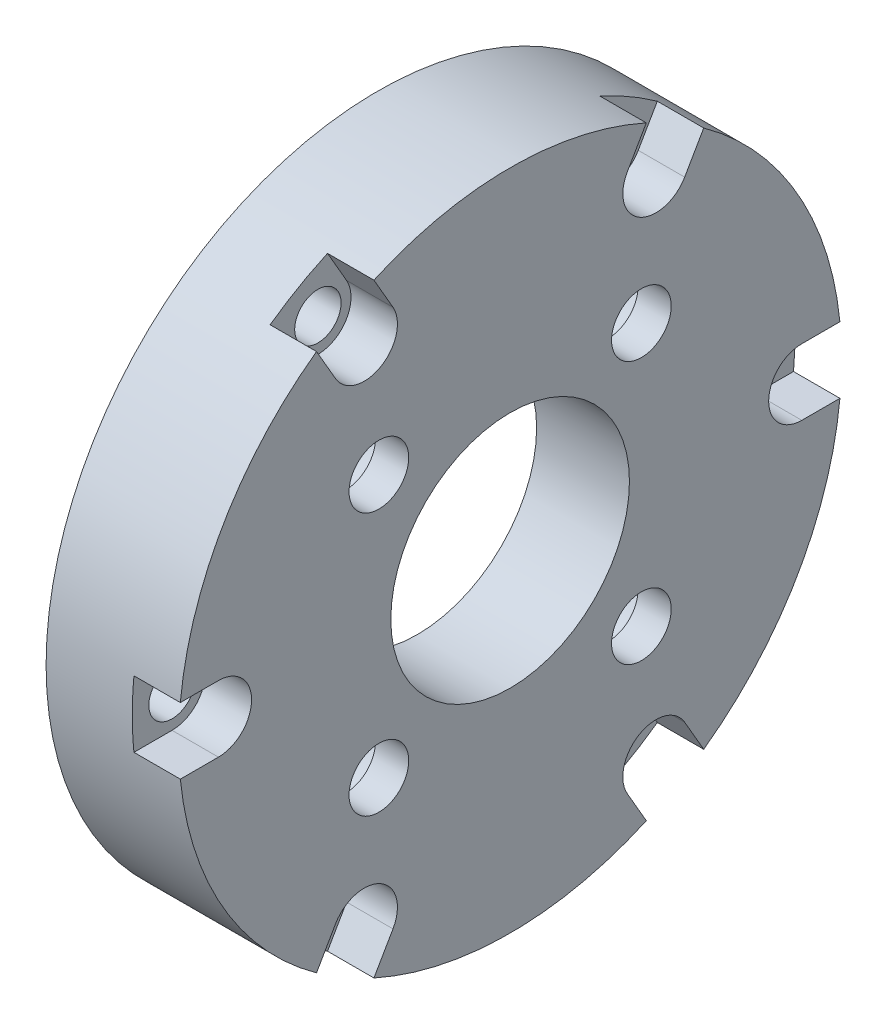
SolidWorks part; units mm, degrees
material "Alliage 1060"
ref_plane "Plan1" through (0, 0, 0) normal (0, 0, 1) x (1, 0, 0)
ref_plane "Plan2" through (0, 0, 0) normal (0, 1, 0) x (1, 0, 0)
ref_plane "Plan3" through (0, 0, 0) normal (1, 0, 0) x (0, 0, -1)
sketch "Esquisse1" plane through (0, 0, 0) normal (0, 0, 1) x (1, 0, 0)
  line L0 (-5, 25) -> (-5, 19)
  line L1 (-5, 19) -> (-2, 19)
  line L2 (-2, 19) -> (-2, 9)
  line L3 (-2, 9) -> (5, 9)
  line L4 (5, 9) -> (5, 25)
  line L5 (5, 25) -> (-5, 25)
  line L15 (-14.9364, 0) -> (44.8605, 0) construction
  dimension "D1" = 10
  dimension "D2" = 3
  dimension "D3" = 25
  dimension "D4" = 9
  dimension "D5" = 2
  dimension "D6" = 19
revolve "Base-Révolution" add sketch "Esquisse1" angle 360 about L15
sketch "Esquisse2" plane through (5, 0, 0) normal (1, 0, 0) x (0, 0, -1)
  line L0 (0, 0) -> (-24.5, 0) construction
  line L1 (-22, 2.5) -> (-25.4352, 2.5)
  line L2 (-22, -2.5) -> (-25.4352, -2.5)
  line L3 (-25.4352, -2.5) -> (-25.4352, 2.5)
  circle A0 centre (0, 0) radius 22 construction
  circle A1 centre (0, 0) radius 25 construction
  arc A2 (-22, -2.5) -> (-22, 2.5) centre (-22, 0) ccw
  dimension "D1" = 44
  dimension "D2" = 5
  dimension "D3" = 25.4352
extrude "Enlèv. mat.-Extru.1" cut sketch "Esquisse2" against normal blind 3.5
pattern_circular "Répétition circulaire1" count 6 every 60 about axis through (0, 0, 0) along (1, 0, 0) of "Enlèv. mat.-Extru.1"
sketch "Esquisse3" plane through (1.5, 0, 0) normal (1, 0, 0) x (0, 0, -1)
  circle A0 centre (-22, 0) radius 1.75
  dimension "D1" = 3.5
extrude "Enlèv. mat.-Extru.2" cut sketch "Esquisse3" against normal through all
pattern_circular "Répétition circulaire2" count 6 every 60 about axis through (0, 0, 0) along (1, 0, 0) of "Enlèv. mat.-Extru.2"
sketch "Esquisse4" plane through (-2, 0, 0) normal (-1, 0, 0) x (0, 0, 1)
  point P0 (9.8995, 9.8995)
hole_wizard "Chambrage pour vis à tête cylindrique à 6 pans creux (vis CHC) M41" positions "Esquisse6" profile "Esquisse5" counterbore size "M4" standard "ISO" end condition through all
sketch "Esquisse6" plane through (-2, 0, 0) normal (-1, 0, 0) x (0, 0, 1)
  point P0 (9.8995, 9.8995)
sketch "Esquisse5" plane through (-2, 9.8995, 9.8995) normal (0, 1, 0) x (0, 0, 1)
  line L0 (0, 0) -> (0, 7)
  line L1 (0, 7) -> (2.25, 7)
  line L3 (2.25, 7) -> (2.25, 4.5)
  line L4 (2.25, 4.5) -> (4, 4.5)
  line L5 (4, 4.5) -> (4, 0)
  line L7 (4, 0) -> (0, 0)
  line L11 (0, -6.35) -> (0, 107.95) construction
  dimension "Diamètre du perçage jusqu'au prochain" = 4.5
  dimension "Profondeur du perçage jusqu'au prochain" = 7
  dimension "Diamètre du chambrage" = 8
  dimension "Profondeur du chambrage" = 4.5
pattern_circular "Répétition circulaire3" count 4 over 360 about axis through (0, 0, 0) along (1, 0, 0) of "Chambrage pour vis à tête cylindrique à 6 pans creux (vis CHC) M41"
